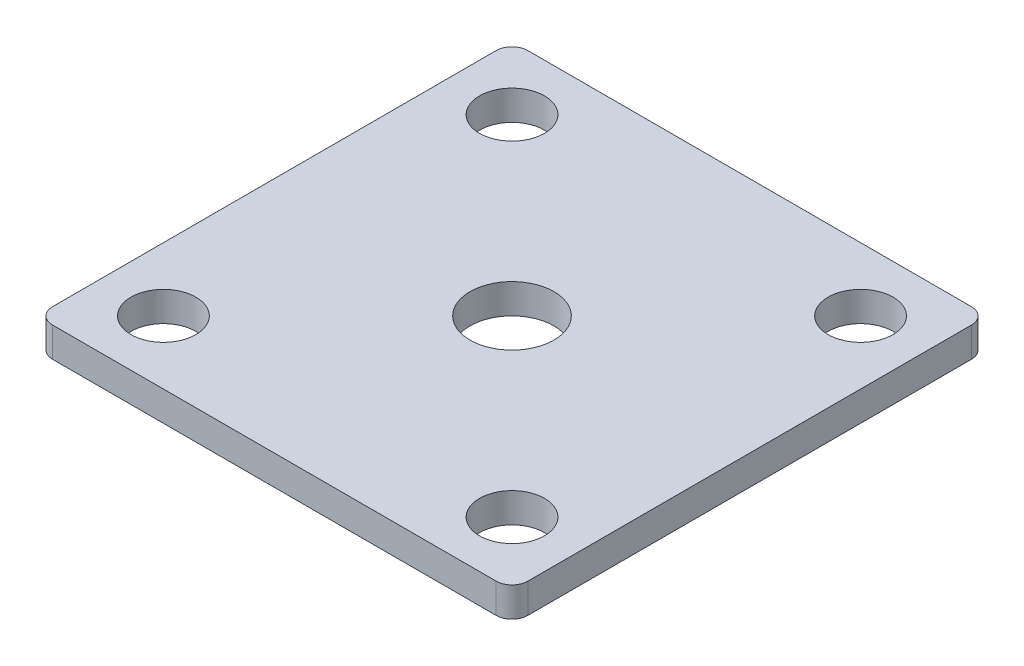
SolidWorks part; units mm, degrees
material "Acrylic (Medium-high impact)"
ref_plane "Front" through (0, 0, 0) normal (0, 0, 1) x (1, 0, 0)
ref_plane "Top" through (0, 0, 0) normal (0, 1, 0) x (1, 0, 0)
ref_plane "Right" through (0, 0, 0) normal (1, 0, 0) x (0, 0, -1)
sketch "Sketch1" plane through (0, 0, 0) normal (0, 0, 1) x (1, 0, 0)
  line L0 (-22.225, 0) -> (22.225, 0)
  dimension "D1" = 44.45
sketch "Sketch2" plane through (0, 0, 0) normal (0, 1, 0) x (1, 0, 0)
  line L0 (-13.97, 13.97) -> (13.97, 13.97) construction
  line L1 (-13.97, 13.97) -> (-13.97, -13.97) construction
  line L2 (-13.97, -13.97) -> (13.97, -13.97) construction
  line L3 (13.97, 13.97) -> (13.97, -13.97) construction
  line L4 (-13.97, 13.97) -> (13.97, -13.97) construction
  line L5 (-13.97, -13.97) -> (13.97, 13.97) construction
  line L7 (-19.05, 19.05) -> (19.05, 19.05)
  line L8 (-19.05, 19.05) -> (-19.05, -19.05)
  line L9 (-19.05, -19.05) -> (19.05, -19.05)
  line L10 (19.05, 19.05) -> (19.05, -19.05)
  line L11 (-19.05, 19.05) -> (19.05, -19.05) construction
  line L12 (-19.05, -19.05) -> (19.05, 19.05) construction
  circle A0 centre (-13.97, 13.97) radius 2.6035
  circle A1 centre (-13.97, -13.97) radius 2.6035
  circle A2 centre (13.97, -13.97) radius 2.6035
  circle A3 centre (13.97, 13.97) radius 2.6035
  circle A4 centre (0, 0) radius 3.3655
  point P0 (0, 0)
  point P12 (0, 0)
  dimension "D3" = 5.207
  dimension "D5" = 6.731
  dimension "D1" = 27.94
  dimension "D2" = 27.94
  dimension "D4" = 38.1
extrude "Boss-Extrude1" add sketch "Sketch2" along normal blind 2.3813
fillet "Fillet1" radius 1.27 4 edges at (-19.05, 1.1906, -19.05) (19.05, 1.1906, -19.05) (19.05, 1.1906, 19.05) (-19.05, 1.1906, 19.05)
